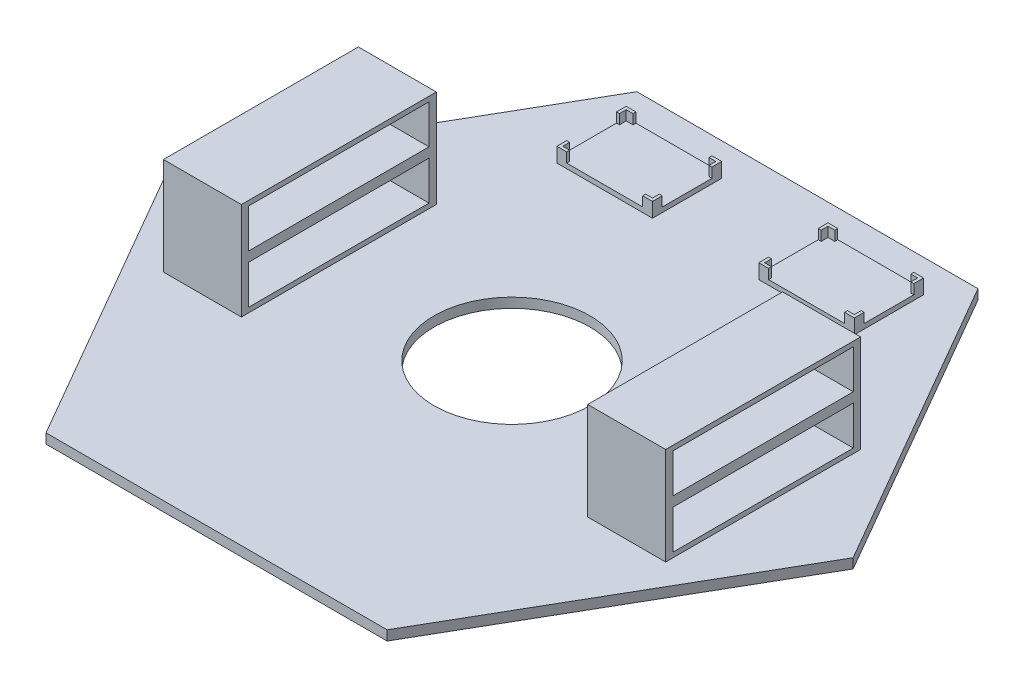
SolidWorks part; units mm, degrees
ref_plane "Front Plane" through (0, 0, 0) normal (0, 0, 1) x (1, 0, 0)
ref_plane "Top Plane" through (0, 0, 0) normal (0, 1, 0) x (1, 0, 0)
ref_plane "Right Plane" through (0, 0, 0) normal (1, 0, 0) x (0, 0, -1)
sketch "Sketch1" plane through (0, 0, 0) normal (0, 1, 0) x (1, 0, 0)
  line L1 (350, 0) -> (175, 303.1089)
  line L2 (175, 303.1089) -> (-175, 303.1089)
  line L3 (-175, 303.1089) -> (-350, 0)
  line L4 (-350, 0) -> (-175, -303.1089)
  line L5 (-175, -303.1089) -> (175, -303.1089)
  line L6 (175, -303.1089) -> (350, 0)
  circle A0 centre (0, 0) radius 350 construction
  dimension "D1" = 700
extrude "Boss-Extrude1" add sketch "Sketch1" along normal blind 10
sketch "Sketch2" plane through (0, 10, 0) normal (0, 1, 0) x (1, 0, 0)
  line L1 (54.5329, 198.6797) -> (152.5329, 198.6797)
  line L2 (54.5329, 198.6797) -> (54.5329, 269.6797)
  line L3 (54.5329, 269.6797) -> (152.5329, 269.6797)
  line L4 (152.5329, 198.6797) -> (152.5329, 269.6797)
  line L5 (54.5329, 198.6797) -> (152.5329, 269.6797) construction
  line L6 (54.5329, 269.6797) -> (152.5329, 198.6797) construction
  line L14 (54.5329, 269.6797) -> (64.5329, 269.6797)
  line L15 (54.5329, 269.6797) -> (54.5329, 266.6797)
  line L16 (54.5329, 266.6797) -> (64.5329, 266.6797)
  line L17 (64.5329, 269.6797) -> (64.5329, 266.6797)
  line L18 (54.5329, 269.6797) -> (57.5329, 269.6797)
  line L19 (54.5329, 269.6797) -> (54.5329, 259.6797)
  line L20 (54.5329, 259.6797) -> (57.5329, 259.6797)
  line L21 (57.5329, 269.6797) -> (57.5329, 259.6797)
  line L23 (54.5329, 198.6797) -> (54.5329, 234.4119)
  line L27 (54.5329, 198.6797) -> (54.5329, 209.2877)
  line L30 (152.5329, 198.6797) -> (142.5329, 198.6797)
  line L31 (152.5329, 198.6797) -> (152.5329, 201.6797)
  line L32 (152.5329, 201.6797) -> (142.5329, 201.6797)
  line L33 (142.5329, 198.6797) -> (142.5329, 201.6797)
  line L34 (152.5329, 198.6797) -> (149.5329, 198.6797)
  line L35 (152.5329, 198.6797) -> (152.5329, 208.6797)
  line L36 (152.5329, 208.6797) -> (149.5329, 208.6797)
  line L37 (149.5329, 198.6797) -> (149.5329, 208.6797)
  line L38 (152.5329, 269.6797) -> (142.5329, 269.6797)
  line L39 (152.5329, 269.6797) -> (152.5329, 266.6797)
  line L40 (152.5329, 266.6797) -> (142.5329, 266.6797)
  line L41 (142.5329, 269.6797) -> (142.5329, 266.6797)
  line L42 (152.5329, 269.6797) -> (149.5329, 269.6797)
  line L43 (152.5329, 269.6797) -> (152.5329, 259.6797)
  line L44 (152.5329, 259.6797) -> (149.5329, 259.6797)
  line L45 (149.5329, 269.6797) -> (149.5329, 259.6797)
  line L77 (0, -5.5) -> (0, 5.5) construction
  line L78 (54.5329, 198.6797) -> (57.5329, 198.6797)
  line L79 (54.5329, 198.6797) -> (54.5329, 208.6797)
  line L80 (54.5329, 208.6797) -> (57.5329, 208.6797)
  line L81 (57.5329, 198.6797) -> (57.5329, 208.6797)
  line L82 (54.5329, 198.6797) -> (64.5329, 198.6797)
  line L83 (54.5329, 198.6797) -> (54.5329, 201.6797)
  line L84 (54.5329, 201.6797) -> (64.5329, 201.6797)
  line L85 (64.5329, 198.6797) -> (64.5329, 201.6797)
  line L86 (-54.5329, 269.6797) -> (-152.5329, 198.6797) construction
  line L87 (-54.5329, 198.6797) -> (-152.5329, 269.6797) construction
  line L88 (-64.5329, 198.6797) -> (-64.5329, 201.6797)
  line L89 (-54.5329, 201.6797) -> (-64.5329, 201.6797)
  line L90 (-54.5329, 198.6797) -> (-54.5329, 201.6797)
  line L91 (-54.5329, 198.6797) -> (-64.5329, 198.6797)
  line L92 (-57.5329, 198.6797) -> (-57.5329, 208.6797)
  line L93 (-54.5329, 208.6797) -> (-57.5329, 208.6797)
  line L94 (-54.5329, 198.6797) -> (-54.5329, 208.6797)
  line L95 (-54.5329, 198.6797) -> (-57.5329, 198.6797)
  line L96 (-149.5329, 269.6797) -> (-149.5329, 259.6797)
  line L97 (-152.5329, 259.6797) -> (-149.5329, 259.6797)
  line L98 (-152.5329, 269.6797) -> (-152.5329, 259.6797)
  line L99 (-152.5329, 269.6797) -> (-149.5329, 269.6797)
  line L100 (-142.5329, 269.6797) -> (-142.5329, 266.6797)
  line L101 (-152.5329, 266.6797) -> (-142.5329, 266.6797)
  line L102 (-152.5329, 269.6797) -> (-152.5329, 266.6797)
  line L103 (-152.5329, 269.6797) -> (-142.5329, 269.6797)
  line L104 (-149.5329, 198.6797) -> (-149.5329, 208.6797)
  line L105 (-152.5329, 208.6797) -> (-149.5329, 208.6797)
  line L106 (-152.5329, 198.6797) -> (-152.5329, 208.6797)
  line L107 (-152.5329, 198.6797) -> (-149.5329, 198.6797)
  line L108 (-142.5329, 198.6797) -> (-142.5329, 201.6797)
  line L109 (-152.5329, 201.6797) -> (-142.5329, 201.6797)
  line L110 (-152.5329, 198.6797) -> (-152.5329, 201.6797)
  line L111 (-152.5329, 198.6797) -> (-142.5329, 198.6797)
  line L112 (-54.5329, 198.6797) -> (-54.5329, 209.2877)
  line L113 (-54.5329, 198.6797) -> (-54.5329, 234.4119)
  line L114 (-57.5329, 269.6797) -> (-57.5329, 259.6797)
  line L115 (-54.5329, 259.6797) -> (-57.5329, 259.6797)
  line L116 (-54.5329, 269.6797) -> (-54.5329, 259.6797)
  line L117 (-54.5329, 269.6797) -> (-57.5329, 269.6797)
  line L118 (-64.5329, 269.6797) -> (-64.5329, 266.6797)
  line L119 (-54.5329, 266.6797) -> (-64.5329, 266.6797)
  line L120 (-54.5329, 269.6797) -> (-54.5329, 266.6797)
  line L121 (-54.5329, 269.6797) -> (-64.5329, 269.6797)
  line L122 (-152.5329, 198.6797) -> (-152.5329, 269.6797)
  line L123 (-54.5329, 269.6797) -> (-152.5329, 269.6797)
  line L124 (-54.5329, 198.6797) -> (-54.5329, 269.6797)
  line L125 (-54.5329, 198.6797) -> (-152.5329, 198.6797)
  circle A0 centre (0, 0) radius 80
  point P3 (103.5329, 234.1797)
  point P66 (-103.5329, 234.1797)
  point P67 (0, 0)
  dimension "D1" = 71
  dimension "D2" = 98
  dimension "D3" = 10
  dimension "D4" = 3
  dimension "D5" = 10
  dimension "D6" = 3
  dimension "D7" = 3
  dimension "D8" = 3
  dimension "D9" = 10
  dimension "D10" = 10
  dimension "D11" = 3
  dimension "D12" = 10
  dimension "D13" = 3
  dimension "D14" = 10
  dimension "D15" = 3
  dimension "D16" = 10
  dimension "D17" = 10
  dimension "D18" = 3
extrude "Boss-Extrude2" add sketch "Sketch2" along normal blind 15 contours L79 L84 L81 L80 | L1 L85 L84 L81 | L84 L2 L1 L81 | L45 L3 L41 L40 | L37 L32 L4 L36 | L21 L3 L2 L16 | L101 L98 L97 L96 | L116 L119 L114 L115 | L91 L92 L89 L88 | L104 L111 L108 L109
sketch "Sketch3" plane through (0, 10, 0) normal (0, 1, 0) x (1, 0, 0)
  circle A0 centre (0, 0) radius 80
extrude "Cut-Extrude1" cut sketch "Sketch3" against normal blind 10
sketch "Sketch4" plane through (0, 10, 0) normal (0, 1, 0) x (1, 0, 0)
  line L1 (-152.5329, 269.6797) -> (-54.5329, 269.6797)
  line L2 (-152.5329, 269.6797) -> (-152.5329, 198.6797)
  line L3 (-152.5329, 198.6797) -> (-54.5329, 198.6797)
  line L4 (-54.5329, 269.6797) -> (-54.5329, 198.6797)
  line L5 (54.5329, 269.6797) -> (152.5329, 269.6797)
  line L6 (54.5329, 269.6797) -> (54.5329, 198.6797)
  line L7 (54.5329, 198.6797) -> (152.5329, 198.6797)
  line L8 (152.5329, 269.6797) -> (152.5329, 198.6797)
extrude "Boss-Extrude3" add sketch "Sketch4" along normal blind 5
sketch "Sketch5" plane through (0, 10, 0) normal (0, 1, 0) x (1, 0, 0)
  line L1 (-257.6477, -100) -> (-177.6477, -100)
  line L2 (-257.6477, -100) -> (-257.6477, 100)
  line L3 (-257.6477, 100) -> (-177.6477, 100)
  line L4 (-177.6477, -100) -> (-177.6477, 100)
  line L5 (-257.6477, -100) -> (-177.6477, 100) construction
  line L6 (-257.6477, 100) -> (-177.6477, -100) construction
  point P0 (-217.6477, 0)
  dimension "D1" = 200
  dimension "D2" = 80
extrude "Boss-Extrude4" add sketch "Sketch5" along normal blind 100
sketch "Sketch6" plane through (-257.6477, 0, 0) normal (-1, 0, 0) x (0, 0, 1)
  line L0 (-100, 10) -> (100, 10) construction
  line L1 (-92.5, 55) -> (92.5, 55)
  line L2 (-92.5, 55) -> (-92.5, 15)
  line L3 (-92.5, 15) -> (92.5, 15)
  line L4 (92.5, 55) -> (92.5, 15)
  line L5 (-92.5, 55) -> (92.5, 15) construction
  line L6 (-92.5, 15) -> (92.5, 55) construction
  line L7 (-92.5, 65) -> (92.5, 65)
  line L8 (-92.5, 65) -> (-92.5, 105)
  line L9 (-92.5, 105) -> (92.5, 105)
  line L10 (92.5, 65) -> (92.5, 105)
  line L11 (-92.5, 65) -> (92.5, 105) construction
  line L12 (-92.5, 105) -> (92.5, 65) construction
  line L13 (100, 110) -> (100, 10) construction
  point P0 (0, 35)
  point P5 (0, 85)
  point P12 (0, 10)
  dimension "D1" = 40
  dimension "D2" = 40
  dimension "D3" = 185
  dimension "D4" = 25
  dimension "D5" = 50
  dimension "D6" = 185
  dimension "D7" = 7.5
extrude "Cut-Extrude2" cut sketch "Sketch6" against normal blind 80
mirror "Mirror1" about plane through (0, 0, 0) normal (1, 0, 0) of "Boss-Extrude4", "Cut-Extrude2"
